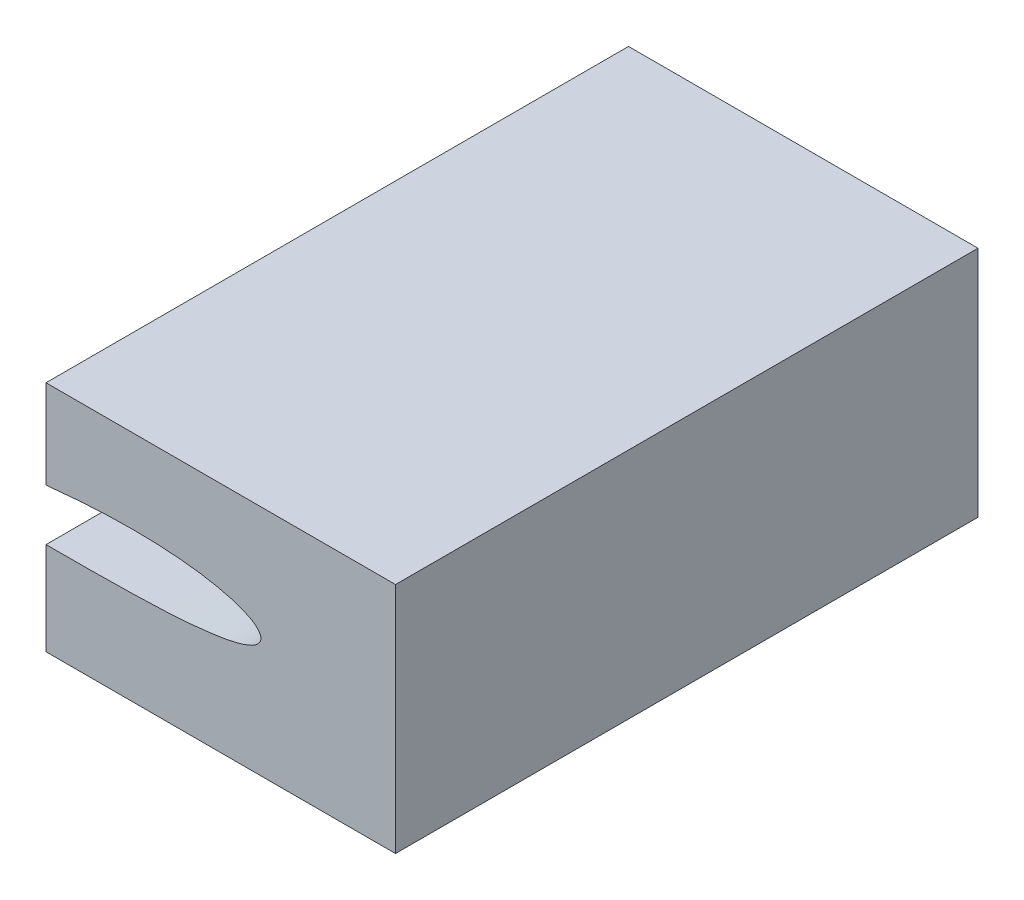
SolidWorks part; units mm, degrees
ref_plane "Front Plane" through (0, 0, 0) normal (0, 0, 1) x (1, 0, 0)
ref_plane "Top Plane" through (0, 0, 0) normal (0, 1, 0) x (1, 0, 0)
ref_plane "Right Plane" through (0, 0, 0) normal (1, 0, 0) x (0, 0, -1)
curve "Curve1"
  spline degree 3 poles (1, 0.0013, 0) (0.9833, 0.0047, 0) (0.9501, 0.0115, 0) (0.8835, 0.024, 0) (0.8002, 0.0379, 0) (0.7002, 0.0522, 0) (0.6002, 0.0641, 0) (0.5001, 0.0729, 0) (0.4001, 0.0788, 0) (0.3166, 0.0798, 0) (0.2499, 0.077, 0) (0.1999, 0.073, 0) (0.1498, 0.0666, 0) (0.108, 0.0587, 0) (0.0748, 0.0498, 0) (0.0496, 0.0416, 0) (0.0282, 0.0322, 0) (0.0098, 0.0207, 0) (-0.0063, 0.0009, 0) (0.0104, -0.0165, 0) (0.0285, -0.0245, 0) (0.0497, -0.0305, 0) (0.0749, -0.0348, 0) (0.1083, -0.0385, 0) (0.1499, -0.0414, 0) (0.2, -0.0425, 0) (0.25, -0.0424, 0) (0.3167, -0.0409, 0) (0.4, -0.0382, 0) (0.5, -0.0336, 0) (0.6, -0.0276, 0) (0.7, -0.0214, 0) (0.8, -0.0151, 0) (0.8833, -0.0093, 0) (0.95, -0.0048, 0) (0.9833, -0.0025, 0) (1, -0.0013, 0) knots 0 0 0 0 0.025012 0.049959 0.099673 0.149206 0.198581 0.247805 0.296917 0.345953 0.370492 0.395091 0.419815 0.444799 0.45749 0.470406 0.483879 0.491264 0.503459 0.513609 0.520451 0.533235 0.545691 0.558032 0.582609 0.607135 0.631652 0.656174 0.705234 0.75432 0.803437 0.852566 0.901701 0.950849 0.975423 1 1 1 1
sketch "Sketch2" plane through (17.4402, 0, 0) normal (0, 0, 1) x (1, 0, 0)
  line L0 (-17.4402, 5.3904) -> (-17.4402, 13)
  line L1 (-17.4402, 0.9686) -> (-17.4402, -7)
  line L2 (-17.4402, 13) -> (12.5598, 13)
  line L4 (-17.4402, -7) -> (12.5598, -7)
  line L5 (12.5598, 13) -> (12.5598, -7)
  spline S0 degree 3 poles (-17.4402, 5.3904) (-16.6649, 5.4708) (-14.5611, 5.6669) (-11.7835, 5.8217) (-9.1134, 5.8277) (-7.1057, 5.7534) (-5.0914, 5.5848) (-3.4106, 5.3423) (-2.0659, 5.0436) (-1.0442, 4.7633) (-0.174, 4.4228) (0.5824, 3.9968) (1.2592, 3.2326) (0.6225, 2.5072) (-0.0862, 2.158) (-0.9256, 1.8797) (-1.9224, 1.6628) (-3.2503, 1.457) (-4.9109, 1.2706) (-6.9089, 1.1377) (-8.9078, 1.0568) (-11.5747, 0.9993) (-14.419, 0.9655) (-16.5966, 0.9651) (-17.4402, 0.9686) knots 0.268255 0.268255 0.268255 0.268255 0.296917 0.345953 0.370492 0.395091 0.419815 0.444799 0.45749 0.470406 0.483879 0.491264 0.503459 0.513609 0.520451 0.533235 0.545691 0.558032 0.582609 0.607135 0.631652 0.656174 0.705234 0.736257 0.736257 0.736257 0.736257
extrude "Boss-Extrude1" add sketch "Sketch2" along normal blind 50 contours L2 L5 L4 L1 S0 L0
